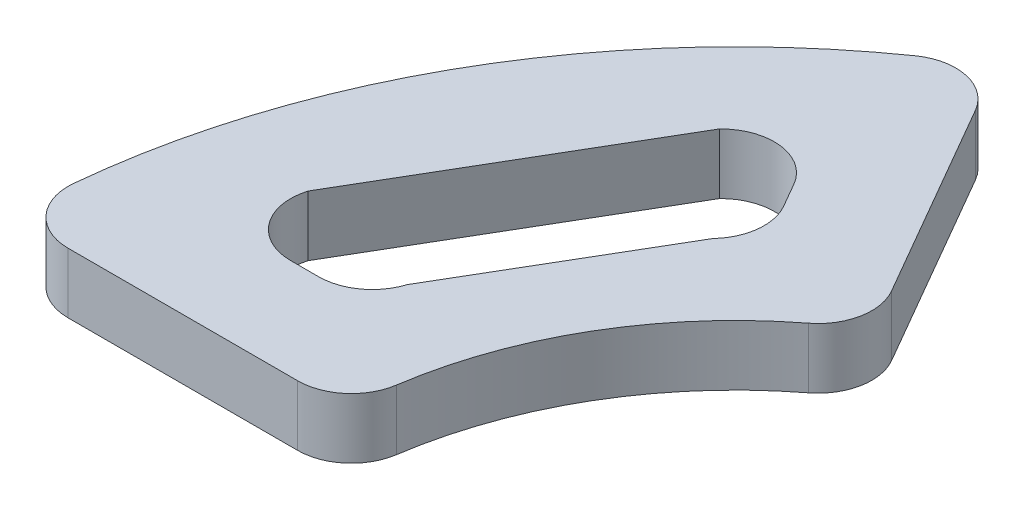
SolidWorks part; units mm, degrees
material "Copper"
ref_plane "Front Plane" through (0, 0, 0) normal (0, 0, 1) x (1, 0, 0)
ref_plane "Top Plane" through (0, 0, 0) normal (0, 1, 0) x (1, 0, 0)
ref_plane "Right Plane" through (0, 0, 0) normal (1, 0, 0) x (0, 0, -1)
sketch "Sketch1" plane through (0, 0, 0) normal (0, 1, 0) x (1, 0, 0)
  line L0 (0, -1498.1409) -> (0, 73408.9065) construction
  line L1 (-1498.1409, 0) -> (73408.9065, 0) construction
  line L2 (-101.5086, 2) -> (-67.2607, 2)
  line L9 (-500, 866.0254) -> (24500, -42435.2448) construction
  line L10 (-50.4931, 55.4567) -> (-60.6779, 73.0972) construction
  line L11 (-34.5669, 57.8717) -> (-51.6671, 87.4901)
  line L12 (-53.5836, 60.8095) -> (-55.6685, 64.4206)
  line L13 (-93.4666, 17) -> (-73.0479, 17) construction
  line L14 (-109.9818, 2) -> (-59.9667, 2) construction
  line L15 (-83.3307, 17) -> (-79.1454, 17)
  line L16 (-30.8619, 51.4543) -> (-55.8638, 94.7589) construction
  line L17 (-54.6793, 51.3339) -> (-71.517, 22.5904)
  line L18 (-68.3527, 65.9766) -> (-90.9933, 27.2989)
  circle A0 centre (0, 0) radius 90 construction
  arc A17 (-93.4666, 17) -> (-60.6779, 73.0972) centre (0, 0) cw construction
  arc A18 (-55.6685, 64.4206) -> (-68.3527, 65.9766) centre (-62.5967, 60.4206) ccw
  arc A19 (-109.4701, 10.7843) -> (-63.191, 90.0383) centre (0, 0) cw
  arc A20 (-59.3477, 8.8235) -> (-36.6133, 47.5338) centre (0, 0) cw
  arc A23 (-73.0479, 17) -> (-50.4931, 55.4567) centre (0, 0) cw construction
  arc A24 (-53.5836, 60.8095) -> (-54.6793, 51.3339) centre (-60.5118, 56.8095) cw
  arc A25 (-71.517, 22.5904) -> (-79.1454, 17) centre (-79.1454, 25) cw
  arc A26 (-83.3307, 17) -> (-90.9933, 27.2989) centre (-83.3307, 25) cw
  arc A27 (-109.9818, 2) -> (-55.8638, 94.7589) centre (0, 0) cw construction
  arc A28 (-109.4701, 10.7843) -> (-101.5086, 2) centre (-101.5086, 10) ccw
  arc A29 (-59.9667, 2) -> (-30.8619, 51.4543) centre (0, 0) cw construction
  arc A30 (-67.2607, 2) -> (-59.3477, 8.8235) centre (-67.2607, 10) ccw
  arc A31 (-34.5669, 57.8717) -> (-36.6133, 47.5338) centre (-41.4951, 53.8717) cw
  arc A32 (-51.6671, 87.4901) -> (-63.191, 90.0383) centre (-58.5953, 83.4901) ccw
  point P10 (-60.6779, 73.0972)
  dimension "D1" = 180
  dimension "D2" = 2
  dimension "D6" = 2
  dimension "D7" = 33.3121
  dimension "D8" = 110
  dimension "D11" = 8
  dimension "D3" = 60
  dimension "D5" = 8
  dimension "D15" = 8
  dimension "D9" = 30
  dimension "D10" = 15
  dimension "D12" = 64.7343
  dimension "D13" = 98.9582
  dimension "D14" = 19.1851
  dimension "D16" = 50.7216
  dimension "D17" = 59.639
  dimension "D18" = 36.8654
extrude "Boss-Extrude1" add sketch "Sketch1" along normal mid plane 9
